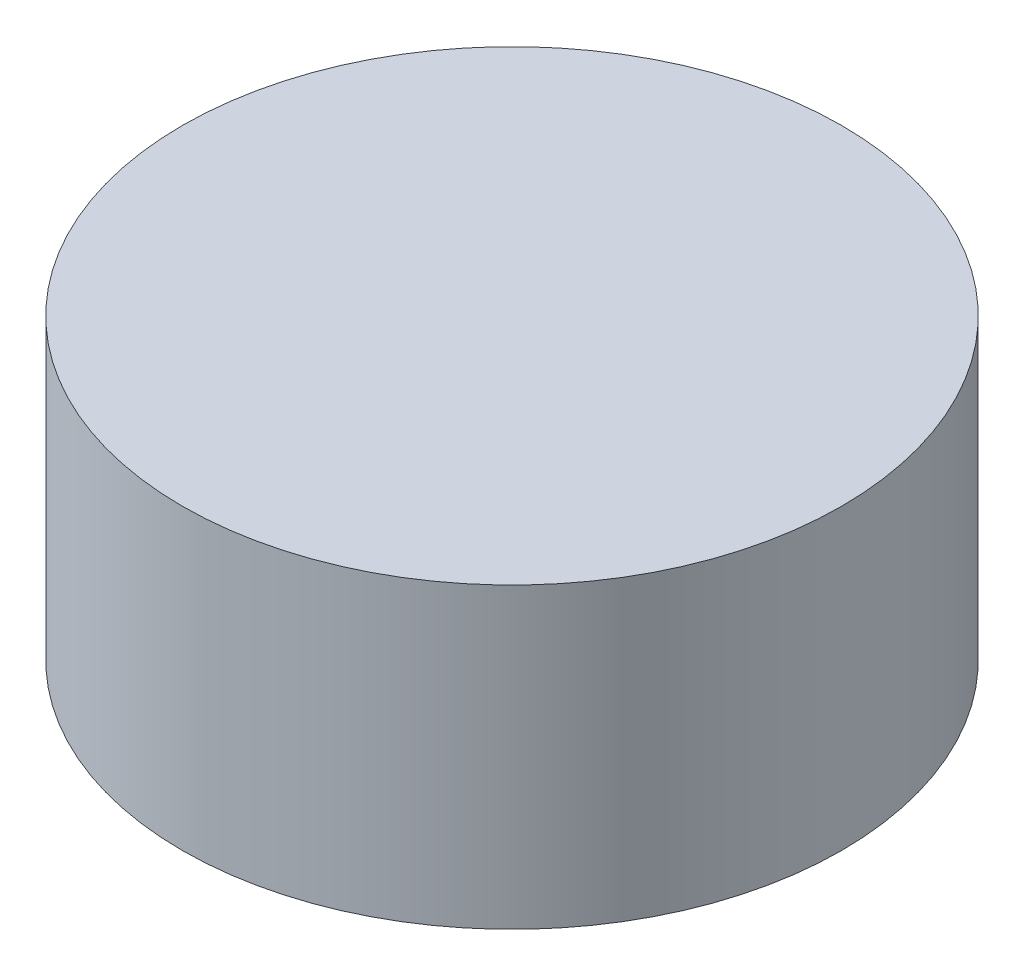
SolidWorks part; units mm, degrees
ref_plane "Front Plane" through (0, 0, 0) normal (0, 0, 1) x (1, 0, 0)
ref_plane "Top Plane" through (0, 0, 0) normal (0, 1, 0) x (1, 0, 0)
ref_plane "Right Plane" through (0, 0, 0) normal (1, 0, 0) x (0, 0, -1)
sketch "Sketch1" plane through (0, 0, 0) normal (0, 1, 0) x (1, 0, 0)
  circle A0 centre (-19.8908, 20.6708) radius 16.5857
extrude "Boss-Extrude1" add sketch "Sketch1" along normal blind 15
